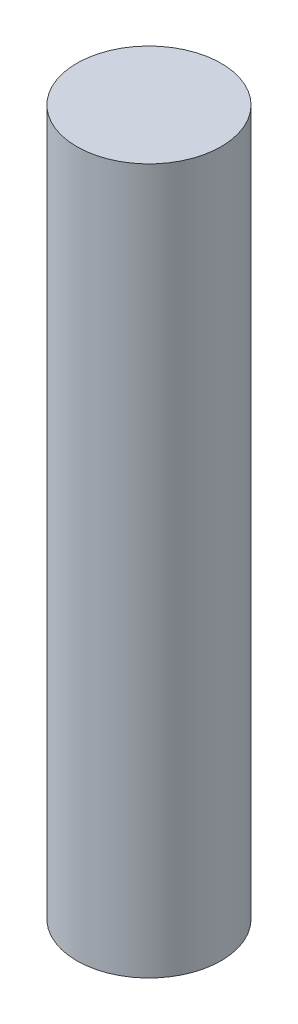
SolidWorks part; units mm, degrees
ref_plane "Front Plane" through (0, 0, 0) normal (0, 0, 1) x (1, 0, 0)
ref_plane "Top Plane" through (0, 0, 0) normal (0, 1, 0) x (1, 0, 0)
ref_plane "Right Plane" through (0, 0, 0) normal (1, 0, 0) x (0, 0, -1)
sketch "Sketch1" plane through (0, 0, 0) normal (0, 1, 0) x (1, 0, 0)
  circle A0 centre (0, 0) radius 3.175
  dimension "D1" = 6.35
extrude "Boss-Extrude1" add sketch "Sketch1" along normal blind 31
